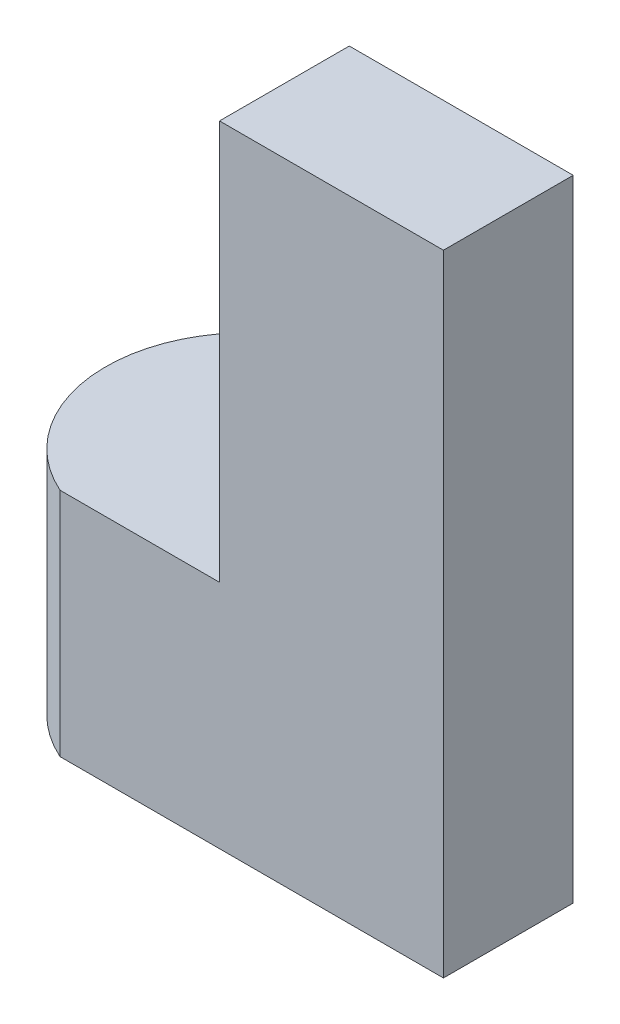
SolidWorks part; units mm, degrees
ref_plane "前视基准面" through (0, 0, 0) normal (0, 0, 1) x (1, 0, 0)
ref_plane "上视基准面" through (0, 0, 0) normal (0, 1, 0) x (1, 0, 0)
ref_plane "右视基准面" through (0, 0, 0) normal (1, 0, 0) x (0, 0, -1)
sketch "草图1" plane through (0, 0, 0) normal (0, 1, 0) x (1, 0, 0)
  line L0 (-25.1102, 16.0261) -> (38.851, 16.0261)
  line L1 (38.851, 16.0261) -> (38.851, -18.9739)
  line L2 (38.851, -18.9739) -> (-64.563, -18.9739)
  line L3 (-25.1102, 46.0792) -> (-25.1102, 16.0261)
  arc A0 (-25.1102, 46.0792) -> (-64.563, -18.9739) centre (-48.915, 16.0261) ccw
  point P1 (0, 0)
  point P8 (-25.1102, 46.0029)
  point P9 (-25.1102, 16.0261)
  point P10 (0, 0)
  dimension "D2" = 35
extrude "凸台-拉伸1" add sketch "草图1" along normal blind 170
sketch "草图3" plane through (0, 0, 18.9739) normal (0, 0, 1) x (1, 0, 0)
  line L1 (-87.7915, 201.9397) -> (-21.5434, 201.9397)
  line L2 (-87.7915, 201.9397) -> (-87.7915, 62.228)
  line L3 (-87.7915, 62.228) -> (-21.5434, 62.228)
  line L4 (-21.5434, 201.9397) -> (-21.5434, 62.228)
extrude "切除-拉伸1" cut sketch "草图3" against normal blind 170
